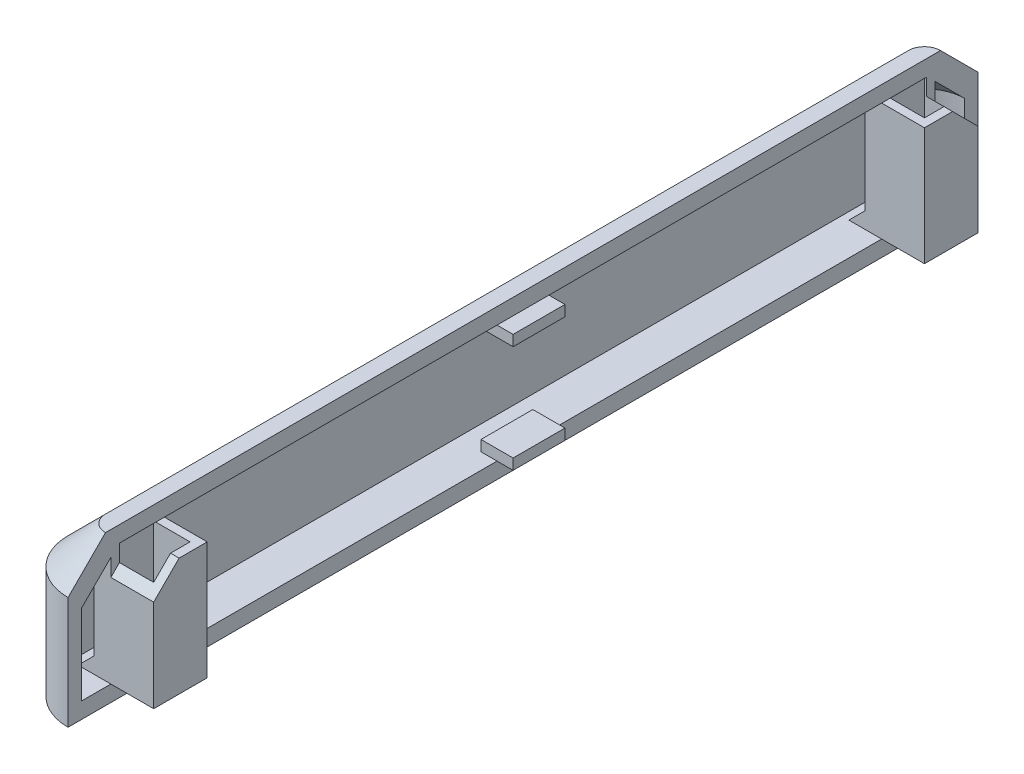
SolidWorks part; units mm, degrees
ref_plane "Front Plane" through (0, 0, 0) normal (0, 0, 1) x (1, 0, 0)
ref_plane "Top Plane" through (0, 0, 0) normal (0, 1, 0) x (1, 0, 0)
ref_plane "Right Plane" through (0, 0, 0) normal (1, 0, 0) x (0, 0, -1)
sketch "Sketch1" plane through (0, 0, 0) normal (0, 1, 0) x (1, 0, 0)
  line L1 (0, 0) -> (315, 0)
  line L2 (0, 0) -> (0, 150)
  line L3 (0, 150) -> (315, 150)
  line L4 (315, 0) -> (315, 150)
  line L5 (157.5, 150) -> (157.5, 0) construction
  line L6 (0, 75) -> (315, 75) construction
  line L7 (11.8793, 83.5932) -> (37.8793, 83.5932)
  line L8 (11.8793, 83.5932) -> (11.8793, 72.5932)
  line L9 (11.8793, 72.5932) -> (37.8793, 72.5932)
  line L10 (37.8793, 83.5932) -> (37.8793, 72.5932)
  line L11 (24.8793, 72.5932) -> (24.8793, 83.5932) construction
  line L12 (11.8793, 78.0932) -> (37.8793, 78.0932) construction
  line L17 (114.9071, 89.45) -> (181.1755, 89.45) construction
  line L18 (65.6251, 144.4154) -> (205.6251, 144.4154)
  line L42 (260.2509, 144.4154) -> (285.2509, 144.4154)
  line L43 (234.1707, 144.4154) -> (259.1707, 144.4154)
  line L44 (234.1707, 144.4154) -> (234.1707, 52.4154)
  line L45 (234.1707, 52.4154) -> (259.1707, 52.4154)
  line L46 (259.1707, 144.4154) -> (259.1707, 52.4154)
  line L47 (246.6707, 52.4154) -> (246.6707, 144.4154) construction
  line L48 (234.1707, 98.4154) -> (259.1707, 98.4154) construction
  line L49 (260.2509, 144.4154) -> (260.2509, 52.4154)
  line L50 (260.2509, 52.4154) -> (285.2509, 52.4154)
  line L51 (285.2509, 144.4154) -> (285.2509, 52.4154)
  line L52 (287.1734, 144.4154) -> (312.1734, 144.4154)
  line L53 (287.1734, 144.4154) -> (287.1734, 52.4154)
  line L54 (287.1734, 52.4154) -> (312.1734, 52.4154)
  line L55 (312.1734, 144.4154) -> (312.1734, 52.4154)
  line L72 (65.6251, 144.4154) -> (65.6251, 124.4154)
  line L73 (65.6251, 124.4154) -> (205.6251, 124.4154)
  line L74 (205.6251, 144.4154) -> (205.6251, 124.4154)
  line L75 (135.6251, 124.4154) -> (135.6251, 144.4154) construction
  line L76 (65.6251, 134.4154) -> (205.6251, 134.4154) construction
  line L81 (65.688, 113.6965) -> (85.688, 113.6965)
  line L82 (65.688, 113.6965) -> (65.688, 33.6965)
  line L83 (10.3843, 23.9694) -> (90.3843, 23.9694)
  line L84 (10.3843, 23.9694) -> (10.3843, 3.9694)
  line L85 (10.3843, 3.9694) -> (90.3843, 3.9694)
  line L86 (90.3843, 23.9694) -> (90.3843, 3.9694)
  line L87 (50.3843, 3.9694) -> (50.3843, 23.9694) construction
  line L88 (10.3843, 13.9694) -> (90.3843, 13.9694) construction
  line L89 (65.688, 33.6965) -> (85.688, 33.6965)
  line L90 (85.688, 113.6965) -> (85.688, 33.6965)
  line L91 (75.688, 33.6965) -> (75.688, 113.6965) construction
  line L92 (65.688, 73.6965) -> (85.688, 73.6965) construction
  line L93 (205.3895, 44.9232) -> (245.3895, 44.9232)
  line L94 (205.3895, 44.9232) -> (205.3895, 4.9232)
  line L95 (205.3895, 4.9232) -> (245.3895, 4.9232)
  line L96 (245.3895, 44.9232) -> (245.3895, 4.9232)
  line L97 (225.3895, 4.9232) -> (225.3895, 44.9232) construction
  line L98 (205.3895, 24.9232) -> (245.3895, 24.9232) construction
  line L99 (245.3895, 44.9232) -> (265.3895, 44.9232)
  line L100 (245.3895, 44.9232) -> (245.3895, 24.9232)
  line L101 (245.3895, 24.9232) -> (265.3895, 24.9232)
  line L102 (265.3895, 44.9232) -> (265.3895, 24.9232)
  line L103 (255.3895, 24.9232) -> (255.3895, 44.9232) construction
  line L104 (245.3895, 34.9232) -> (265.3895, 34.9232) construction
  line L105 (181.1755, 89.45) -> (181.1755, 24.3783) construction
  line L106 (181.1755, 24.3783) -> (114.9071, 24.3783) construction
  line L107 (33.5208, 117.195) -> (33.5208, 48.1962) construction
  line L109 (273.3018, 34.1392) -> (307.3018, 34.1392)
  line L110 (273.3018, 34.1392) -> (273.3018, 8.1392)
  line L111 (273.3018, 8.1392) -> (307.3018, 8.1392)
  line L112 (307.3018, 34.1392) -> (307.3018, 8.1392)
  line L113 (290.3018, 8.1392) -> (290.3018, 34.1392) construction
  line L114 (273.3018, 21.1392) -> (307.3018, 21.1392) construction
  line L115 (117.5413, 65.9142) -> (178.5413, 65.9142)
  line L116 (117.5413, 65.9142) -> (117.5413, 47.9142)
  line L117 (117.5413, 47.9142) -> (178.5413, 47.9142)
  line L118 (178.5413, 65.9142) -> (178.5413, 47.9142)
  line L119 (148.0413, 47.9142) -> (148.0413, 65.9142) construction
  line L120 (117.5413, 56.9142) -> (178.5413, 56.9142) construction
  line L121 (5.8793, 85.7294) -> (45.8793, 85.7294)
  line L122 (5.8793, 85.7294) -> (5.8793, 70.457)
  line L123 (5.8793, 70.457) -> (45.8793, 70.457)
  line L124 (45.8793, 85.7294) -> (45.8793, 70.457)
  line L125 (25.8793, 70.457) -> (25.8793, 85.7294) construction
  line L126 (5.8793, 78.0932) -> (45.8793, 78.0932) construction
  circle A0 centre (33.5208, 117.195) radius 27.5
  circle A1 centre (33.5208, 48.1962) radius 20
  circle A2 centre (114.9071, 24.3783) radius 20
  circle A3 centre (114.9071, 89.45) radius 20
  circle A4 centre (181.1755, 24.3783) radius 20
  circle A5 centre (181.1755, 89.45) radius 20
  point P38 (148.0413, 56.9142)
  point P42 (148.0413, 89.45)
  point P56 (181.1755, 56.9142)
  point P57 (25.8793, 78.0932)
  point P195 (24.8793, 78.0932)
  point P224 (290.3018, 21.1392)
  point P252 (246.6707, 98.4154)
  point P259 (225.3895, 24.9232)
  point P417 (255.3895, 34.9232)
  point P438 (75.688, 73.6965)
  point P456 (157.5, 75)
  point P559 (50.3843, 13.9694)
  point P704 (135.6251, 134.4154)
  dimension "D3" = 55
  dimension "D6" = 40
  dimension "D1" = 150
  dimension "D2" = 315
  dimension "D4" = 26
  dimension "D5" = 11
  dimension "D7" = 20
  dimension "D8" = 140
  dimension "D9" = 25
  dimension "D10" = 92
  dimension "D11" = 20
  dimension "D12" = 80
  dimension "D13" = 20
  dimension "D14" = 80
  dimension "D15" = 40
  dimension "D16" = 40
  dimension "D17" = 20
  dimension "D18" = 34
  dimension "D19" = 26
  dimension "D20" = 61
  dimension "D21" = 18
  dimension "D22" = 6
  dimension "D23" = 8
  dimension "D24" = 25
  dimension "D25" = 25
sketch "Sketch2" plane through (0, 0, 0) normal (0, 1, 0) x (1, 0, 0)
  line L1 (0, 150) -> (6, 150)
  line L2 (0, 150) -> (0, 144)
  line L3 (0, 144) -> (6, 144)
  line L4 (6, 150) -> (6, 144)
  line L5 (3, 144) -> (3, 150) construction
  line L6 (0, 147) -> (6, 147) construction
  line L8 (0, 6) -> (6, 6)
  line L9 (0, 6) -> (0, 0)
  line L10 (0, 0) -> (6, 0)
  line L11 (6, 6) -> (6, 0)
  line L12 (3, 0) -> (3, 6) construction
  line L13 (0, 3) -> (6, 3) construction
  line L25 (157.5848, 119.0301) -> (163.5848, 119.0301)
  line L26 (157.5848, 119.0301) -> (157.5848, 113.0301)
  line L31 (157.5848, 113.0301) -> (163.5848, 113.0301)
  line L32 (163.5848, 119.0301) -> (163.5848, 113.0301)
  line L37 (160.5848, 113.0301) -> (160.5848, 119.0301) construction
  line L38 (157.5848, 116.0301) -> (163.5848, 116.0301) construction
  line L43 (143.8527, 27.0473) -> (153.8527, 27.0473)
  line L44 (143.8527, 27.0473) -> (143.8527, 17.0473)
  line L49 (143.8527, 17.0473) -> (153.8527, 17.0473)
  line L50 (153.8527, 27.0473) -> (153.8527, 17.0473)
  line L55 (148.8527, 17.0473) -> (148.8527, 27.0473) construction
  line L56 (143.8527, 22.0473) -> (153.8527, 22.0473) construction
  line L68 (146.1081, 11.4408) -> (152.1081, 11.4408)
  line L73 (146.1081, 11.4408) -> (146.1081, 5.4408)
  line L74 (103.2441, 63.6402) -> (113.2441, 63.6402)
  line L75 (309, 6) -> (315, 6)
  line L76 (309, 6) -> (309, 0)
  line L77 (309, 0) -> (315, 0)
  line L78 (315, 6) -> (315, 0)
  line L79 (312, 0) -> (312, 6) construction
  line L80 (309, 3) -> (315, 3) construction
  line L85 (103.2441, 63.6402) -> (103.2441, 53.6402)
  line L86 (103.2441, 53.6402) -> (113.2441, 53.6402)
  line L87 (309, 150) -> (315, 150)
  line L88 (309, 150) -> (309, 144)
  line L89 (309, 144) -> (315, 144)
  line L90 (315, 150) -> (315, 144)
  line L91 (312, 144) -> (312, 150) construction
  line L92 (309, 147) -> (315, 147) construction
  line L93 (113.2441, 63.6402) -> (113.2441, 53.6402)
  line L94 (108.2441, 53.6402) -> (108.2441, 63.6402) construction
  line L95 (103.2441, 58.6402) -> (113.2441, 58.6402) construction
  line L96 (49.7601, 81.4098) -> (59.7601, 81.4098)
  line L97 (49.7601, 81.4098) -> (49.7601, 71.4098)
  line L98 (49.7601, 71.4098) -> (59.7601, 71.4098)
  line L99 (59.7601, 81.4098) -> (59.7601, 71.4098)
  line L100 (54.7601, 71.4098) -> (54.7601, 81.4098) construction
  line L101 (49.7601, 76.4098) -> (59.7601, 76.4098) construction
  line L102 (51.8887, 38.6479) -> (61.8887, 38.6479)
  line L103 (51.8887, 38.6479) -> (51.8887, 28.6479)
  line L104 (51.8887, 28.6479) -> (61.8887, 28.6479)
  line L105 (61.8887, 38.6479) -> (61.8887, 28.6479)
  line L106 (56.8887, 28.6479) -> (56.8887, 38.6479) construction
  line L107 (51.8887, 33.6479) -> (61.8887, 33.6479) construction
  line L108 (1.6875, 66.969) -> (11.6875, 66.969)
  line L109 (1.6875, 66.969) -> (1.6875, 56.969)
  line L110 (1.6875, 56.969) -> (11.6875, 56.969)
  line L111 (11.6875, 66.969) -> (11.6875, 56.969)
  line L112 (6.6875, 56.969) -> (6.6875, 66.969) construction
  line L113 (1.6875, 61.969) -> (11.6875, 61.969) construction
  line L114 (100.3283, 117.374) -> (110.3283, 117.374)
  line L115 (100.3283, 117.374) -> (100.3283, 107.374)
  line L116 (100.3283, 107.374) -> (110.3283, 107.374)
  line L117 (110.3283, 117.374) -> (110.3283, 107.374)
  line L118 (105.3283, 107.374) -> (105.3283, 117.374) construction
  line L119 (100.3283, 112.374) -> (110.3283, 112.374) construction
  line L120 (191.7316, 63.7001) -> (201.7316, 63.7001)
  line L121 (191.7316, 63.7001) -> (191.7316, 53.7001)
  line L122 (191.7316, 53.7001) -> (201.7316, 53.7001)
  line L123 (201.7316, 63.7001) -> (201.7316, 53.7001)
  line L124 (196.7316, 53.7001) -> (196.7316, 63.7001) construction
  line L125 (191.7316, 58.7001) -> (201.7316, 58.7001) construction
  line L130 (146.1081, 5.4408) -> (152.1081, 5.4408)
  line L131 (152.1081, 11.4408) -> (152.1081, 5.4408)
  line L132 (255.4879, 16.7818) -> (265.4879, 16.7818)
  line L133 (255.4879, 16.7818) -> (255.4879, 6.7818)
  line L134 (255.4879, 6.7818) -> (265.4879, 6.7818)
  line L135 (265.4879, 16.7818) -> (265.4879, 6.7818)
  line L136 (260.4879, 6.7818) -> (260.4879, 16.7818) construction
  line L137 (255.4879, 11.7818) -> (265.4879, 11.7818) construction
  line L138 (285.0588, 48.1735) -> (295.0588, 48.1735)
  line L139 (285.0588, 48.1735) -> (285.0588, 38.1735)
  line L140 (285.0588, 38.1735) -> (295.0588, 38.1735)
  line L141 (295.0588, 48.1735) -> (295.0588, 38.1735)
  line L142 (290.0588, 38.1735) -> (290.0588, 48.1735) construction
  line L143 (285.0588, 43.1735) -> (295.0588, 43.1735) construction
  line L144 (143.296, 91.7052) -> (153.296, 91.7052)
  line L145 (143.296, 91.7052) -> (143.296, 81.7052)
  line L146 (143.296, 81.7052) -> (153.296, 81.7052)
  line L147 (153.296, 91.7052) -> (153.296, 81.7052)
  line L148 (148.296, 81.7052) -> (148.296, 91.7052) construction
  line L149 (143.296, 86.7052) -> (153.296, 86.7052) construction
  line L150 (201.1129, 112.1386) -> (211.1129, 112.1386)
  line L151 (201.1129, 112.1386) -> (201.1129, 102.1386)
  line L152 (201.1129, 102.1386) -> (211.1129, 102.1386)
  line L153 (211.1129, 112.1386) -> (211.1129, 102.1386)
  line L154 (206.1129, 102.1386) -> (206.1129, 112.1386) construction
  line L155 (201.1129, 107.1386) -> (211.1129, 107.1386) construction
  line L156 (149.1081, 5.4408) -> (149.1081, 11.4408) construction
  line L157 (146.1081, 8.4408) -> (152.1081, 8.4408) construction
  circle A0 centre (3, 147) radius 1.6
  circle A1 centre (3, 3) radius 1.6
  circle A12 centre (312, 3) radius 1.6
  circle A14 centre (312, 147) radius 1.6
  circle A16 centre (160.5848, 116.0301) radius 1.6
  circle A17 centre (148.8527, 22.0473) radius 3
  circle A19 centre (108.2441, 58.6402) radius 3
  circle A20 centre (54.7601, 76.4098) radius 3
  circle A21 centre (56.8887, 33.6479) radius 3
  circle A22 centre (6.6875, 61.969) radius 3
  circle A23 centre (105.3283, 112.374) radius 3
  circle A24 centre (196.7316, 58.7001) radius 3
  circle A26 centre (260.4879, 11.7818) radius 3
  circle A27 centre (290.0588, 43.1735) radius 3
  circle A28 centre (148.296, 86.7052) radius 3
  circle A29 centre (206.1129, 107.1386) radius 3
  circle A30 centre (149.1081, 8.4408) radius 1.6
  dimension "D1" = 3.2
  dimension "D4" = 3.2
  dimension "D6" = 3.2
  dimension "D8" = 3.2
  dimension "D9" = 3.2
  dimension "D12" = 6
  dimension "D15" = 6
  dimension "D18" = 3.2
  dimension "D2" = 6
  dimension "D3" = 6
  dimension "D5" = 6
  dimension "D7" = 6
  dimension "D10" = 6
  dimension "D11" = 6
  dimension "D13" = 10
  dimension "D14" = 10
  dimension "D16" = 10
  dimension "D17" = 10
  dimension "D19" = 6
sketch "Sketch3" plane through (0, 0, 0) normal (0, 1, 0) x (1, 0, 0)
  line L0 (0, 160) -> (0, -10)
  line L1 (-10, 150) -> (-10, 0)
  arc A0 (0, 160) -> (-10, 150) centre (0, 150) ccw
  arc A1 (0, -10) -> (-10, 0) centre (0, 0) cw
  dimension "D1" = 10
  dimension "D2" = 10
extrude "Boss-Extrude1" add sketch "Sketch3" along normal blind 28
shell "Shell1" thickness 2.5
chamfer "Chamfer1" distance 7 angle 45 6 edges at (-5.3033, 25, -155.3033) (-5.3033, 25, 5.3033) (-7.5, 25, -75) (-7.0711, 28, 7.0711) (-7.0711, 28, -157.0711) (-10, 28, -75)
sketch "Sketch6" plane through (0, 3, 0) normal (0, 1, 0) x (1, 0, 0)
  line L0 (0, 147) -> (6, 147) construction
  line L1 (8, 152) -> (-3.122, 152)
  line L2 (8, 152) -> (8, 142)
  line L3 (8, 142) -> (-3.122, 142)
  line L4 (-3.122, 152) -> (-3.122, 142)
  line L5 (2.439, 142) -> (2.439, 152) construction
  line L6 (8, 147) -> (-3.122, 147) construction
  line L7 (6, 150) -> (6, 144) construction
  line L8 (0, 150) -> (315, 150) construction
  line L10 (0, 75) -> (64.3275, 75) construction
  line L11 (-0.4, 143.6) -> (6.4, 143.6)
  line L12 (-0.4, 143.6) -> (-0.4, 150.4)
  line L13 (-0.4, 150.4) -> (6.4, 150.4)
  line L14 (6.4, 143.6) -> (6.4, 150.4)
  line L15 (3, 150.4) -> (3, 143.6) construction
  line L16 (-0.4, 147) -> (6.4, 147) construction
  line L17 (0, 75) -> (315, 75) construction
  line L18 (-0.4, 3) -> (6.4, 3) construction
  line L19 (3, -0.4) -> (3, 6.4) construction
  line L20 (8, 3) -> (-3.122, 3) construction
  line L21 (2.439, 8) -> (2.439, -2) construction
  line L22 (6.4, 6.4) -> (6.4, -0.4)
  line L23 (-0.4, -0.4) -> (6.4, -0.4)
  line L24 (-0.4, 6.4) -> (-0.4, -0.4)
  line L25 (-0.4, 6.4) -> (6.4, 6.4)
  line L26 (-3.122, -2) -> (-3.122, 8)
  line L27 (8, 8) -> (-3.122, 8)
  line L28 (8, -2) -> (8, 8)
  line L29 (8, -2) -> (-3.122, -2)
  point P10 (3, 147)
  point P34 (2.439, 3)
  point P35 (3, 3)
  point P512 (2.439, 147)
  dimension "D1" = 2
  dimension "D2" = 2
  dimension "D3" = 0.4
  dimension "D4" = 0.4
extrude "Boss-Extrude2" add sketch "Sketch6" along normal up to surface (22 mm away) up to face at (-0.3018, 25, -75)
chamfer "Chamfer2" distance 3 angle 45 2 edges at (-3.122, 3, -147) (-3.122, 3, -3)
sketch "Sketch7" plane through (8, 0, 0) normal (1, 0, 0) x (0, 0, -1)
  line L0 (-3.2903, 29.7732) -> (-3.2903, 18.9607)
  line L1 (-3.2903, 18.9607) -> (4.4561, 26.7071)
  line L2 (4.4561, 26.7071) -> (-3.2903, 29.7732)
  line L3 (75, 28) -> (75, 46.451) construction
  line L4 (-3, 28) -> (153, 28) construction
  line L5 (145.5439, 26.7071) -> (153.2903, 29.7732)
  line L6 (153.2903, 18.9607) -> (145.5439, 26.7071)
  line L7 (153.2903, 29.7732) -> (153.2903, 18.9607)
extrude "Cut-Extrude2" cut sketch "Sketch7" against normal up to surface (8 mm away)
sketch "Sketch8" plane through (0, 0, 0) normal (1, 0, 0) x (0, 0, -1)
  line L0 (75, 3) -> (75, 8.811) construction
  line L1 (8, 3) -> (142, 3) construction
  line L2 (150, 3) -> (0, 3) construction
  line L3 (70.1483, 3) -> (79.8332, 3)
  line L4 (70.1483, 3) -> (70.1483, 5)
  line L5 (70.1483, 5) -> (79.8332, 5)
  line L6 (79.8332, 3) -> (79.8332, 5)
  line L7 (74.9908, 5) -> (74.9908, 3) construction
  line L8 (70.1483, 4) -> (79.8332, 4) construction
  line L9 (8, 25) -> (142, 25) construction
  line L10 (70.1483, 25) -> (79.8332, 25)
  line L11 (70.1483, 25) -> (70.1483, 23)
  line L12 (70.1483, 23) -> (79.8332, 23)
  line L13 (79.8332, 25) -> (79.8332, 23)
  line L14 (74.9908, 23) -> (74.9908, 25) construction
  line L15 (70.1483, 24) -> (79.8332, 24) construction
  point P270 (74.9908, 24)
  point P324 (74.9908, 4)
  dimension "D1" = 2
  dimension "D2" = 2
extrude "Boss-Extrude3" add sketch "Sketch8" along normal blind 3 and the other way blind 3
